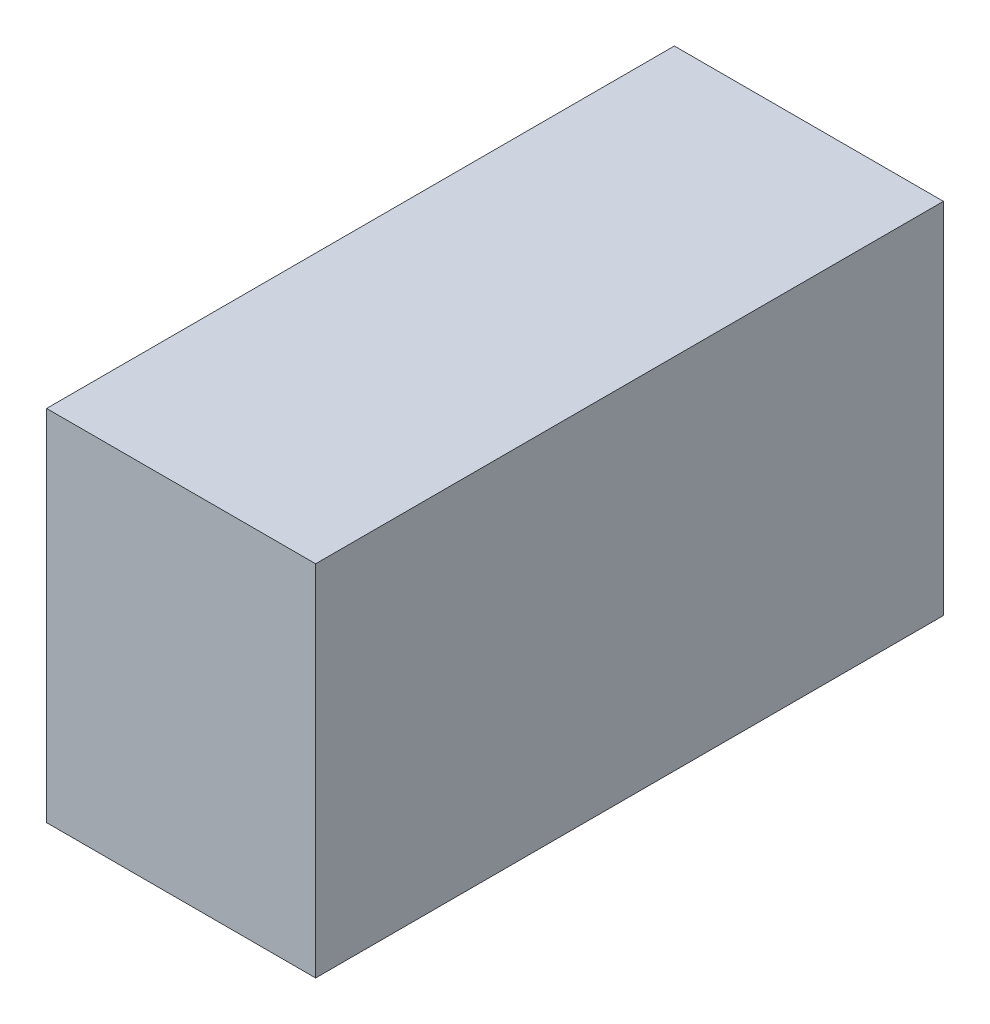
SolidWorks part; units mm, degrees
material "Pine"
ref_plane "Front Plane" through (0, 0, 0) normal (0, 0, 1) x (1, 0, 0)
ref_plane "Top Plane" through (0, 0, 0) normal (0, 1, 0) x (1, 0, 0)
ref_plane "Right Plane" through (0, 0, 0) normal (1, 0, 0) x (0, 0, -1)
sketch "Sketch1" plane through (0, 0, 0) normal (0, 1, 0) x (1, 0, 0)
  line L1 (0, 0) -> (38.1, 0)
  line L2 (0, 0) -> (0, 88.9)
  line L3 (0, 88.9) -> (38.1, 88.9)
  line L4 (38.1, 0) -> (38.1, 88.9)
  dimension "D1" = 38.1
  dimension "D2" = 88.9
extrude "Boss-Extrude1" add sketch "Sketch1" along normal blind 50.8
